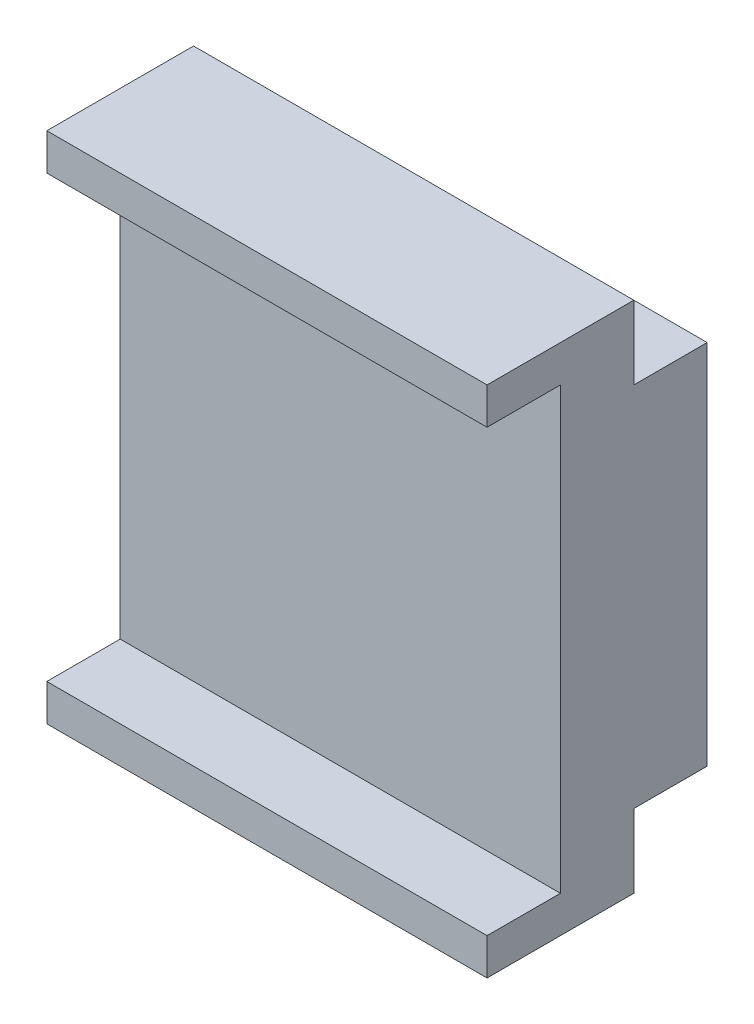
SolidWorks part; units mm, degrees
ref_plane "Front Plane" through (0, 0, 0) normal (0, 0, 1) x (1, 0, 0)
ref_plane "Top Plane" through (0, 0, 0) normal (0, 1, 0) x (1, 0, 0)
ref_plane "Right Plane" through (0, 0, 0) normal (1, 0, 0) x (0, 0, -1)
sketch "Sketch1" plane through (0, 0, 0) normal (1, 0, 0) x (0, 0, -1)
  line L1 (0, 0) -> (5, 0)
  line L2 (0, 0) -> (0, 35)
  line L3 (0, 35) -> (5, 35)
  line L4 (5, 0) -> (5, 35)
  line L5 (5, 5) -> (10, 5)
  line L6 (5, 5) -> (5, 30)
  line L7 (5, 30) -> (10, 30)
  line L8 (10, 5) -> (10, 30)
  line L9 (0, 35) -> (-5, 35)
  line L10 (0, 35) -> (0, 32.5)
  line L11 (0, 32.5) -> (-5, 32.5)
  line L12 (-5, 35) -> (-5, 32.5)
  line L13 (0, 0) -> (-5, 0)
  line L14 (0, 0) -> (0, 2.5)
  line L15 (0, 2.5) -> (-5, 2.5)
  line L16 (-5, 0) -> (-5, 2.5)
  dimension "D1" = 35
  dimension "D2" = 25
  dimension "D3" = 10
  dimension "D4" = 5
  dimension "D5" = 5
  dimension "D6" = 5
  dimension "D7" = 5
  dimension "D8" = 30
  dimension "D9" = 2.5
extrude "Boss-Extrude1" add sketch "Sketch1" along normal blind 30 contours L5 L8 L7 L4 | L1 L4 L3 L2 | L9 L12 L11 L2 | L16 L13 L2 L15
sketch "Sketch2" plane through (0, 0, -10) normal (0, 0, -1) x (-1, 0, 0)
  line L0 (-30, 30) -> (0, 30) construction
  line L1 (-30, 5) -> (-30, 30) construction
  circle A0 centre (-15, 17.5) radius 10
  point P4 (-30, 17.5)
  dimension "D1" = 20
  dimension "D2" = 12.5
  dimension "D3" = 15
